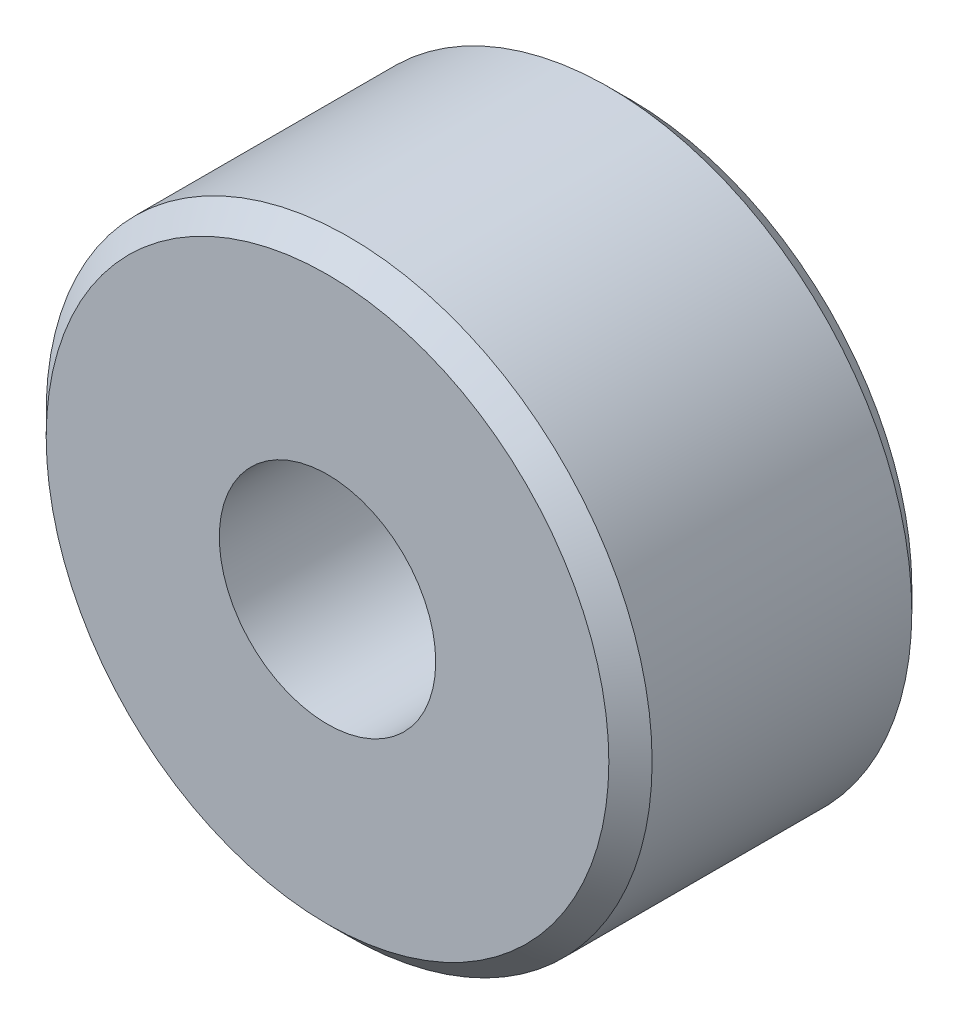
SolidWorks part; units mm, degrees
material "ABS PC"
ref_plane "Front Plane" through (0, 0, 0) normal (0, 0, 1) x (1, 0, 0)
ref_plane "Top Plane" through (0, 0, 0) normal (0, 1, 0) x (1, 0, 0)
ref_plane "Right Plane" through (0, 0, 0) normal (1, 0, 0) x (0, 0, -1)
sketch "Sketch1" plane through (0, 0, 0) normal (0, 0, 1) x (1, 0, 0)
  circle A0 centre (0, 0) radius 0.5
  circle A1 centre (0, 0) radius 1.4
  dimension "D1" = 1
  dimension "D2" = 2.8
extrude "Boss-Extrude1" add sketch "Sketch1" along normal blind 1.4
chamfer "Chamfer1" distance 0.1 angle 45 3 edges at (0.5, 0, 0) (1.4, 0, 0) (1.4, 0, 1.4)
